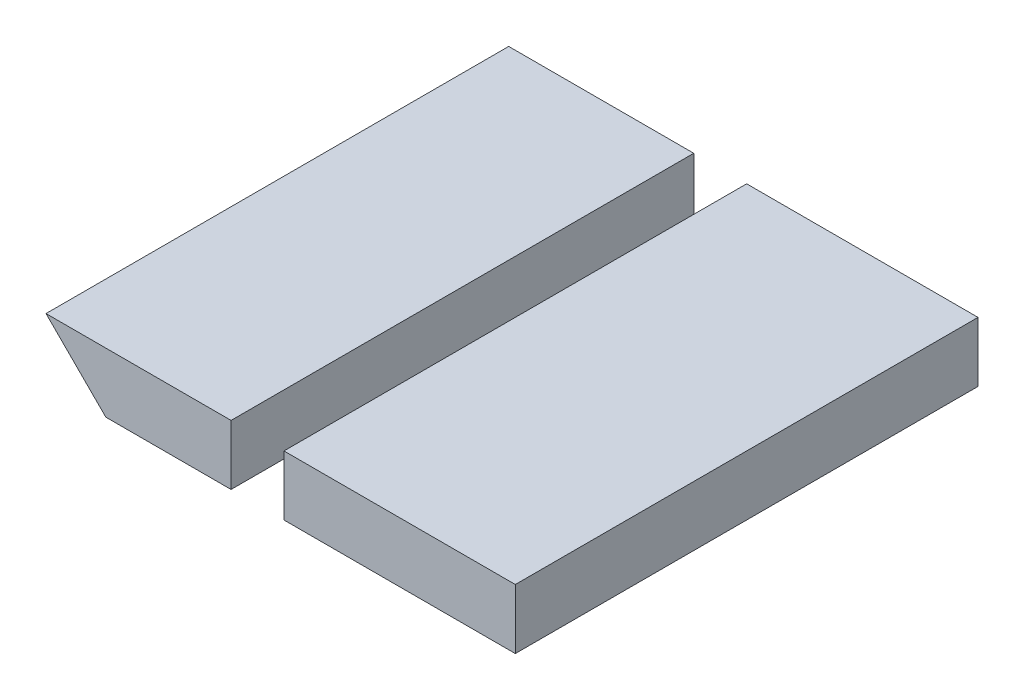
SolidWorks part; units mm, degrees
ref_plane "Plan de face" through (0, 0, 0) normal (0, 0, 1) x (1, 0, 0)
ref_plane "Plan de dessus" through (0, 0, 0) normal (0, 1, 0) x (1, 0, 0)
ref_plane "Plan de droite" through (0, 0, 0) normal (1, 0, 0) x (0, 0, -1)
sketch "Sketch1" plane through (0, 0, 0) normal (0, 0, 1) x (1, 0, 0)
  line L0 (-15.2861, 15.2861) -> (15.2861, 15.2861)
  line L1 (-12.7, -12.7) -> (12.7, -12.7)
  line L2 (-12.7, -12.7) -> (-12.7, 12.7)
  line L3 (-12.7, 12.7) -> (12.7, 12.7)
  line L4 (12.7, -12.7) -> (12.7, 12.7)
  line L5 (-12.7, -12.7) -> (12.7, 12.7) construction
  line L6 (-12.7, 12.7) -> (12.7, -12.7) construction
  line L7 (15.2861, -15.2861) -> (15.2861, 15.2861)
  line L8 (-15.2861, -15.2861) -> (15.2861, -15.2861)
  line L9 (-15.2861, -15.2861) -> (-15.2861, 15.2861)
  line L10 (-15.2861, 15.2861) -> (-12.7, 12.7)
  line L11 (-7.2861, 15.2861) -> (-7.2861, 12.7)
  line L12 (-7.2861, 12.7) -> (-5, 12.7)
  line L13 (-5, 12.7) -> (-5, 15.2861)
  line L14 (-5, 15.2861) -> (5, 15.2861)
  line L15 (5, 15.2861) -> (5, 12.7)
  line L16 (12.7, 12.7) -> (15.2861, 15.2861)
  line L17 (7.2861, 12.7) -> (7.2861, 15.2861)
  line L18 (-7.2861, 15.2861) -> (-5, 15.2861)
  line L19 (5, 15.2861) -> (7.2861, 15.2861)
  line L21 (-15.2861, -15.2861) -> (-12.7, -12.7)
  point P0 (0, 0)
  dimension "D1" = 25.4
  dimension "D3" = 8
  dimension "D4" = 8
  dimension "D5" = 10
  dimension "D2" = 2.5861
extrude "Boss-Extrude1" add sketch "Sketch1" along normal blind 20 contours L11 L0 L10 L3 | L15 L0 L13 L3
equation "\"D2@Sketch1\"=(0.25in - 0.007in - 1.0)/2"
